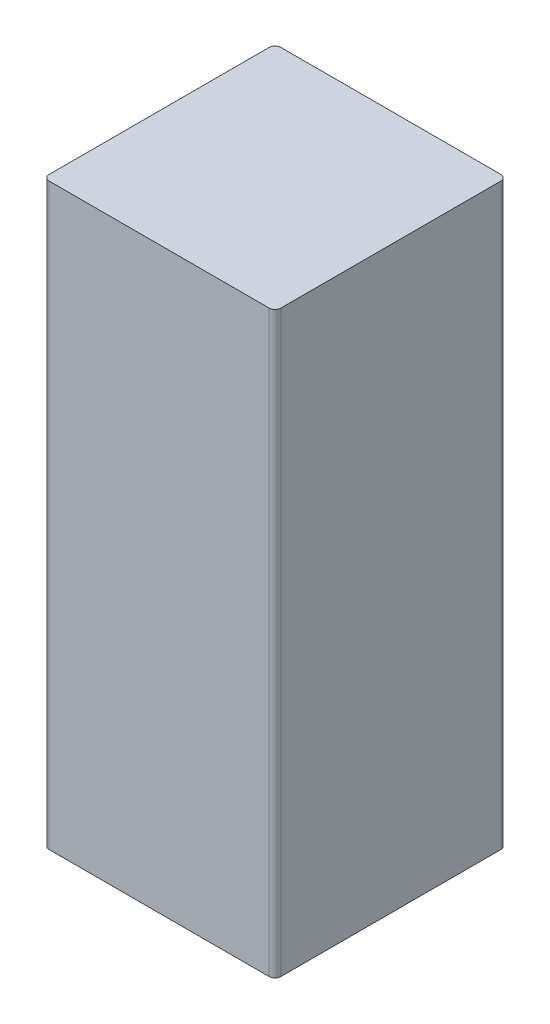
SolidWorks part; units mm, degrees
ref_plane "Front Plane" through (0, 0, 0) normal (0, 0, 1) x (1, 0, 0)
ref_plane "Top Plane" through (0, 0, 0) normal (0, 1, 0) x (1, 0, 0)
ref_plane "Right Plane" through (0, 0, 0) normal (1, 0, 0) x (0, 0, -1)
sketch "Sketch1" plane through (0, 0, 0) normal (0, 1, 0) x (1, 0, 0)
  line L1 (-1.9, -2) -> (1.9, -2)
  line L2 (-2, -1.9) -> (-2, 1.9)
  line L3 (-1.9, 2) -> (1.9, 2)
  line L4 (2, -1.9) -> (2, 1.9)
  line L5 (-2, -2) -> (2, 2) construction
  line L6 (-2, 2) -> (2, -2) construction
  arc A0 (1.9, -2) -> (2, -1.9) centre (1.9, -1.9) ccw
  arc A1 (-1.9, -2) -> (-2, -1.9) centre (-1.9, -1.9) cw
  arc A2 (1.9, 2) -> (2, 1.9) centre (1.9, 1.9) cw
  arc A3 (-2, 1.9) -> (-1.9, 2) centre (-1.9, 1.9) cw
  point P0 (0, 0)
  dimension "D3" = 0.1
  dimension "D1" = 4
  dimension "D2" = 4
extrude "Boss-Extrude1" add sketch "Sketch1" along normal blind 10
